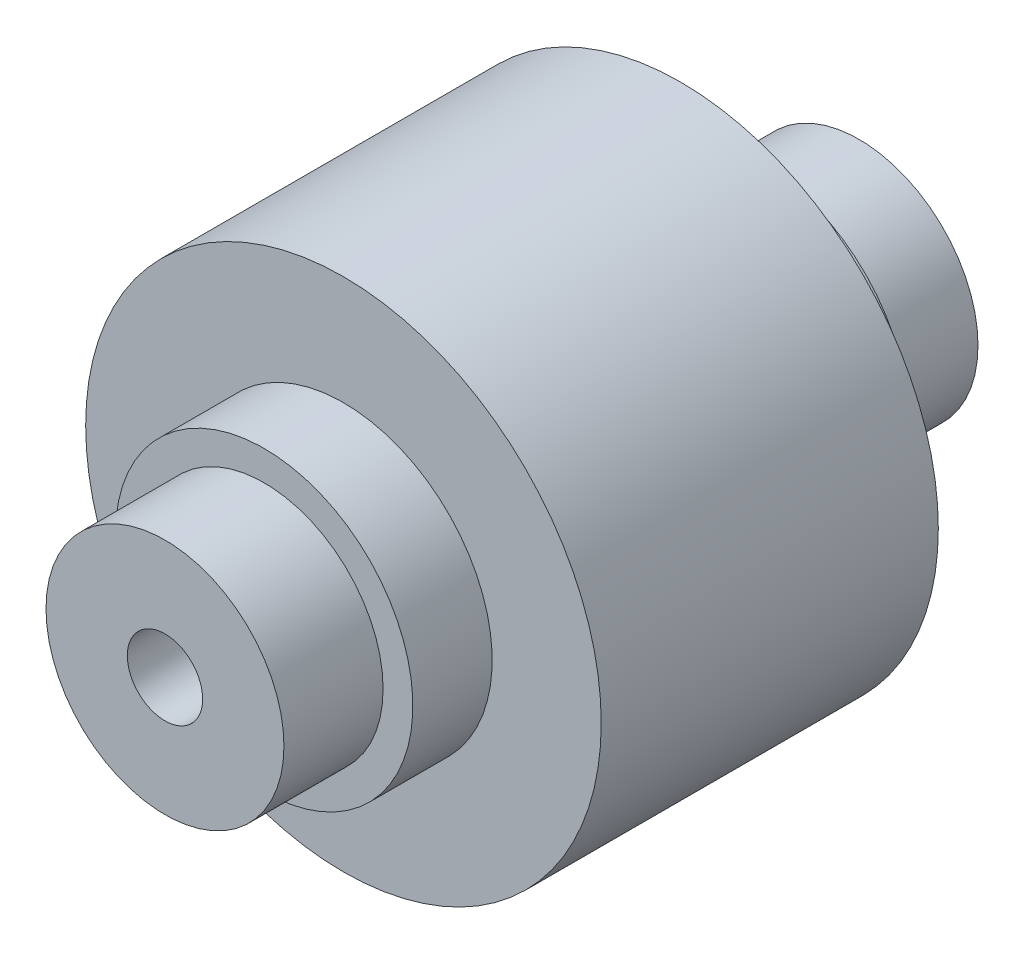
SolidWorks part; units mm, degrees
ref_plane "前视基准面" through (0, 0, 0) normal (0, 0, 1) x (1, 0, 0)
ref_plane "上视基准面" through (0, 0, 0) normal (0, 1, 0) x (1, 0, 0)
ref_plane "右视基准面" through (0, 0, 0) normal (1, 0, 0) x (0, 0, -1)
sketch "草图1" plane through (0, 0, 0) normal (0, 1, 0) x (1, 0, 0)
  line L0 (0, 0) -> (0, -35)
  line L1 (9, -9) -> (13, -9)
  line L2 (9, -26) -> (7.5, -26)
  line L3 (0, -17.5) -> (33.1572, -17.5) construction
  line L4 (6, -30) -> (6, -35)
  line L5 (6, -35) -> (0, -35)
  line L6 (7.5, -26) -> (7.5, -30)
  line L7 (7.5, -30) -> (6, -30)
  line L8 (9, -26) -> (13, -26)
  line L9 (13, -26) -> (13, -9)
  line L10 (7.5, -5) -> (6, -5)
  line L11 (7.5, -9) -> (7.5, -5)
  line L12 (6, 0) -> (0, 0)
  line L13 (6, -5) -> (6, 0)
  line L14 (9, -9) -> (7.5, -9)
  point P10 (13, -17.5)
revolve "旋转1" add sketch "草图1" angle 360 about L0
sketch "草图2" plane through (0, 0, 35) normal (0, 0, 1) x (1, 0, 0)
  circle A0 centre (0, 0) radius 1.9
extrude "切除-拉伸1" cut sketch "草图2" against normal blind 36
